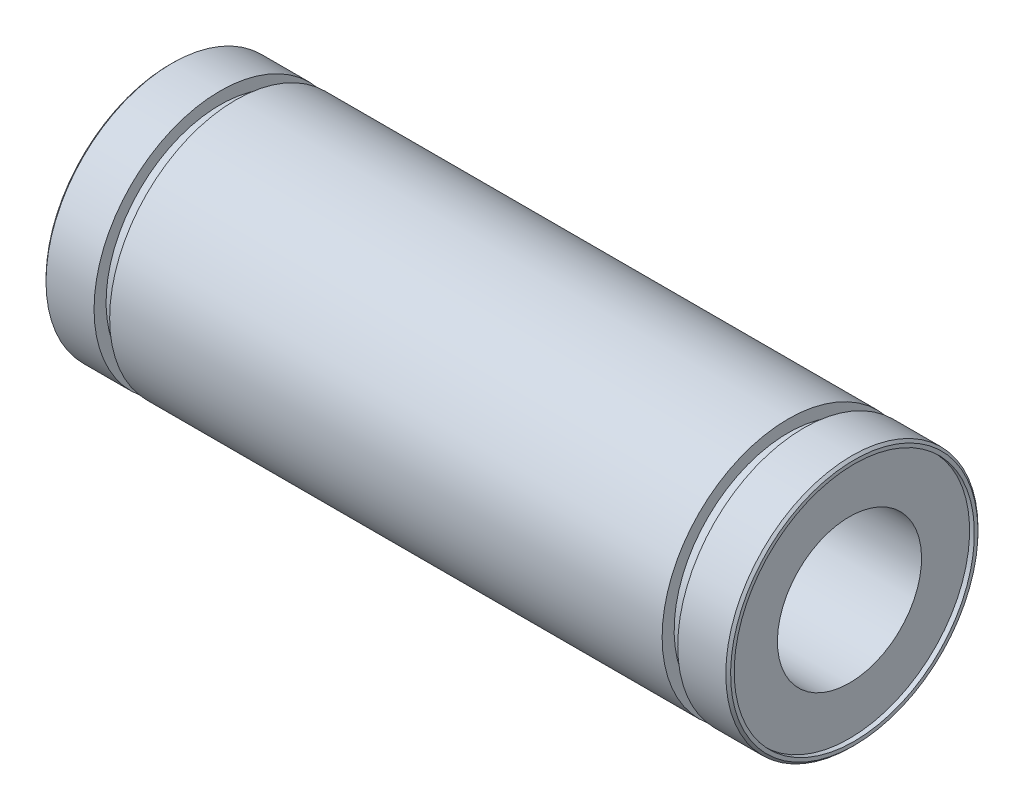
SolidWorks part; units mm, degrees
ref_plane "Front Plane" through (0, 0, 0) normal (0, 0, 1) x (1, 0, 0)
ref_plane "Top Plane" through (0, 0, 0) normal (0, 1, 0) x (1, 0, 0)
ref_plane "Right Plane" through (0, 0, 0) normal (1, 0, 0) x (0, 0, -1)
sketch "Sketch1" plane through (0, 0, 0) normal (0, 0, 1) x (1, 0, 0)
  line L0 (-28.5, 0) -> (28.5, 0) construction
  line L1 (28.5, 0) -> (28.5, 10.3)
  line L2 (28.3, 10.5) -> (24.3, 10.5)
  line L3 (24.3, 10.5) -> (24.3, 9.5)
  line L4 (24.3, 9.5) -> (23, 9.5)
  line L5 (23, 9.5) -> (23, 10.5)
  line L6 (23, 10.5) -> (-23, 10.5)
  line L7 (0, 10.5) -> (0, 0) construction
  line L8 (28.5, 10.3) -> (28.3, 10.5)
  line L9 (-28.1, 6) -> (28.1, 6)
  line L10 (28.1, 6) -> (28.1, 10)
  line L11 (28.1, 10) -> (28.5, 10)
  line L12 (-28.1, 10) -> (-28.5, 10)
  line L13 (-28.1, 6) -> (-28.1, 10)
  line L14 (-28.5, 10.3) -> (-28.3, 10.5)
  line L15 (28.5, 0) -> (-28.5, 0) construction
  line L16 (-23, 9.5) -> (-23, 10.5)
  line L17 (-24.3, 9.5) -> (-23, 9.5)
  line L18 (-24.3, 10.5) -> (-24.3, 9.5)
  line L19 (-28.3, 10.5) -> (-24.3, 10.5)
  line L20 (-28.5, 0) -> (-28.5, 10.3)
  point P4 (28.5, 10.5)
  point P21 (0, 6)
  point P27 (-28.5, 10.5)
  dimension "D1" = 1.3
  dimension "D2" = 1
  dimension "D4" = 10.5
  dimension "D5" = 6
  dimension "D6" = 10
  dimension "D7" = 0.4
  dimension "D8" = 57
  dimension "D9" = 46
revolve "Revolve2" add sketch "Sketch1" angle 360 about L0
